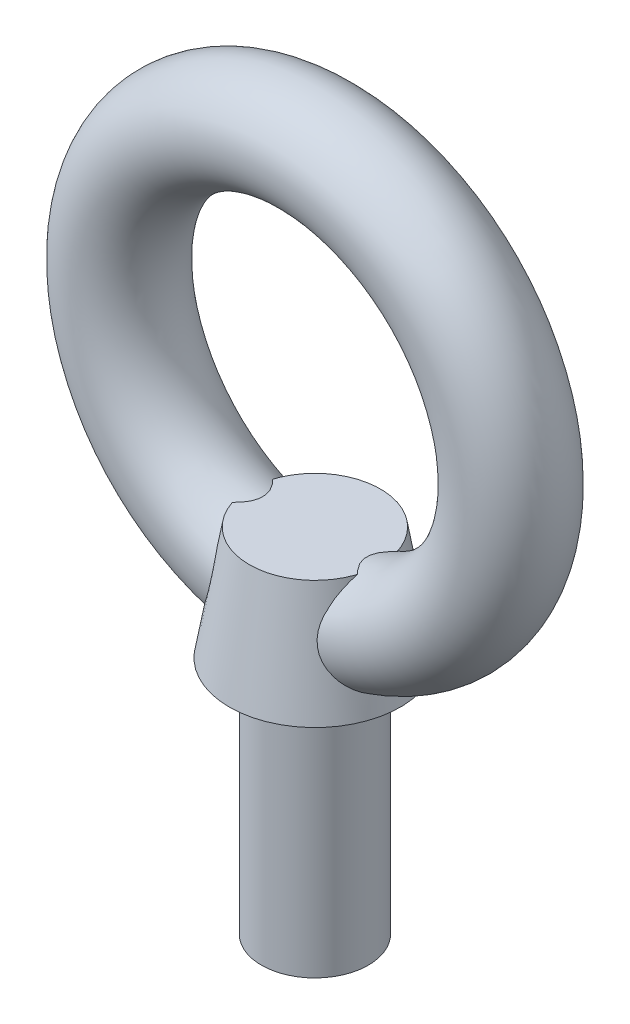
SolidWorks part; units mm, degrees
ref_plane "Plan de face" through (0, 0, 0) normal (0, 0, 1) x (1, 0, 0)
ref_plane "Plan de dessus" through (0, 0, 0) normal (0, 1, 0) x (1, 0, 0)
ref_plane "Plan de droite" through (0, 0, 0) normal (1, 0, 0) x (0, 0, -1)
sketch "Esquisse2" plane through (0, 0, 0) normal (0, 1, 0) x (1, 0, 0)
  line L1 (0, 0) -> (0, 4.38) construction
  line L2 (0, 0) -> (9.155, 0) construction
  circle A0 centre (9.155, 0) radius 2.4
  dimension "D1" = 4.8
  dimension "D2" = 9.155
revolve "Révolution1" add sketch "Esquisse2" angle 360 about L1
sketch "Esquisse3" plane through (0, 0, 0) normal (0, 1, 0) x (1, 0, 0)
  circle A0 centre (0, 0) radius 4
  dimension "D1" = 8
extrude "Boss.-Extru.1" add sketch "Esquisse3" along normal blind 5.3 draft 10 from offset 11.6 separate body offset against normal yes
sketch "Esquisse4" plane through (0, -11.6, 0) normal (0, -1, 0) x (1, 0, 0)
  circle A0 centre (0, 0) radius 2.5
  dimension "D1" = 5
extrude "Boss.-Extru.2" add sketch "Esquisse4" along normal blind 11.2
